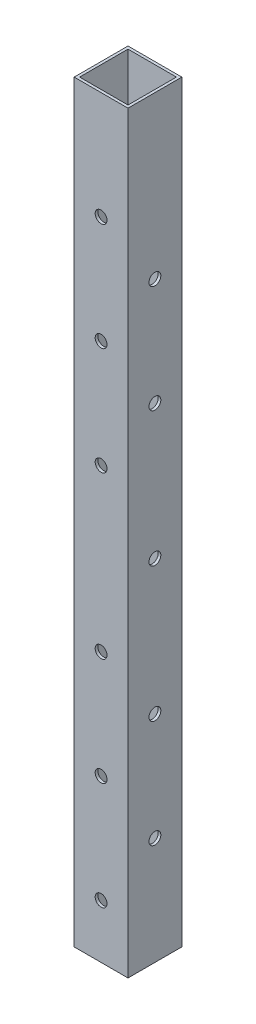
SolidWorks part; units mm, degrees
ref_plane "前视基准面" through (0, 0, 0) normal (0, 0, 1) x (1, 0, 0)
ref_plane "上视基准面" through (0, 0, 0) normal (0, 1, 0) x (1, 0, 0)
ref_plane "右视基准面" through (0, 0, 0) normal (1, 0, 0) x (0, 0, -1)
sketch "草图1" plane through (0, 0, 0) normal (0, 1, 0) x (1, 0, 0)
  line L2 (10, 0) -> (10, 10)
  line L3 (0, 10) -> (10, 10)
  line L6 (9, 0) -> (9, 9)
  line L7 (0, 9) -> (9, 9)
  line L8 (0, -10) -> (10, -10)
  line L9 (10, 0) -> (10, -10)
  line L10 (0, -9) -> (9, -9)
  line L11 (9, 0) -> (9, -9)
  line L12 (-10, 0) -> (-10, -10)
  line L13 (0, -10) -> (-10, -10)
  line L14 (-9, 0) -> (-9, -9)
  line L15 (0, -9) -> (-9, -9)
  line L16 (0, 10) -> (-10, 10)
  line L17 (-10, 0) -> (-10, 10)
  line L18 (0, 9) -> (-9, 9)
  line L19 (-9, 0) -> (-9, 9)
  point P27 (0, 0)
extrude "凸台-拉伸1" add sketch "草图1" against normal blind 280
sketch "草图2" plane through (0, 0, 10) normal (0, 0, 1) x (1, 0, 0)
  circle A0 centre (0, -40) radius 2.2
  circle A1 centre (0, -80) radius 2.2
  circle A2 centre (0, -120) radius 2.2
  circle A3 centre (0, -180) radius 2.2
  circle A4 centre (0, -220) radius 2.2
  circle A5 centre (0, -260) radius 2.2
  dimension "D1" = 3
  dimension "D2" = 2
  dimension "D3" = 3
extrude "切除-拉伸1" cut sketch "草图2" against normal blind 280
sketch "草图3" plane through (10, 0, 0) normal (1, 0, 0) x (0, 0, -1)
  circle A0 centre (0, -60) radius 2.2
  circle A1 centre (0, -100) radius 2.2
  circle A2 centre (0, -150) radius 2.2
  circle A3 centre (0, -200) radius 2.2
  circle A4 centre (0, -240) radius 2.2
extrude "切除-拉伸2" cut sketch "草图3" against normal blind 20
